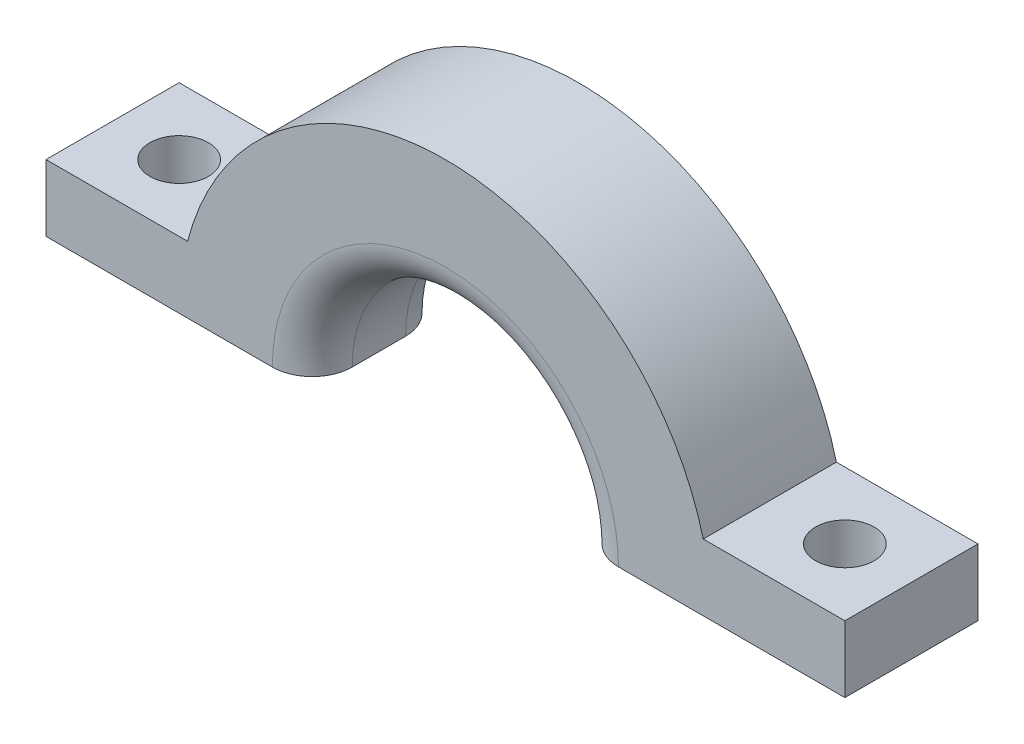
SolidWorks part; units mm, degrees
ref_plane "Front Plane" through (0, 0, 0) normal (0, 0, 1) x (1, 0, 0)
ref_plane "Top Plane" through (0, 0, 0) normal (0, 1, 0) x (1, 0, 0)
ref_plane "Right Plane" through (0, 0, 0) normal (1, 0, 0) x (0, 0, -1)
sketch "Sketch1" plane through (0, 0, 0) normal (0, 1, 0) x (1, 0, 0)
  line L0 (0, 0) -> (0, 30) construction
  line L1 (-20, 0) -> (-13, 0)
  line L2 (-20, 0) -> (-20, 10)
  line L3 (-20, 10) -> (-13, 10)
  line L4 (-10, 3) -> (-10, 7)
  arc A0 (-13, 0) -> (-10, 3) centre (-13, 3) ccw
  arc A1 (-13, 10) -> (-10, 7) centre (-13, 7) cw
  point P9 (-10, 0)
  dimension "D5" = 3
  dimension "D1" = 30
  dimension "D2" = 10
  dimension "D3" = 10
  dimension "D4" = 10
revolve "Revolve1" add sketch "Sketch1" angle 180 about L0
sketch "Sketch2" plane through (0, 0, 0) normal (0, -1, 0) x (1, 0, 0)
  line L0 (13, -10) -> (20, -10) construction
  line L1 (-20, 0) -> (-30, 0)
  line L3 (-20, -10) -> (-30, -10)
  line L4 (-30, 0) -> (-30, -10)
  line L5 (20, 0) -> (30, 0)
  line L7 (20, -10) -> (30, -10)
  line L8 (30, 0) -> (30, -10)
  line L9 (-13, -10) -> (-20, -10) construction
  line L10 (-30, 0) -> (-20, -10) construction
  line L11 (20, -10) -> (30, 0) construction
  line L12 (20, 0) -> (16.5, 0)
  line L13 (-20, 0) -> (-16.5, 0)
  line L15 (-20, -10) -> (-16.5, -10)
  line L16 (-16.5, 0) -> (-16.5, -10)
  line L17 (20, -10) -> (16.5, -10)
  line L18 (16.5, 0) -> (16.5, -10)
  circle A0 centre (-25, -5) radius 2.2
  circle A1 centre (25, -5) radius 2.2
  dimension "D3" = 4.4
  dimension "D4" = 4.4
  dimension "D1" = 10
  dimension "D2" = 10
extrude "Boss-Extrude1" add sketch "Sketch2" against normal blind 5
